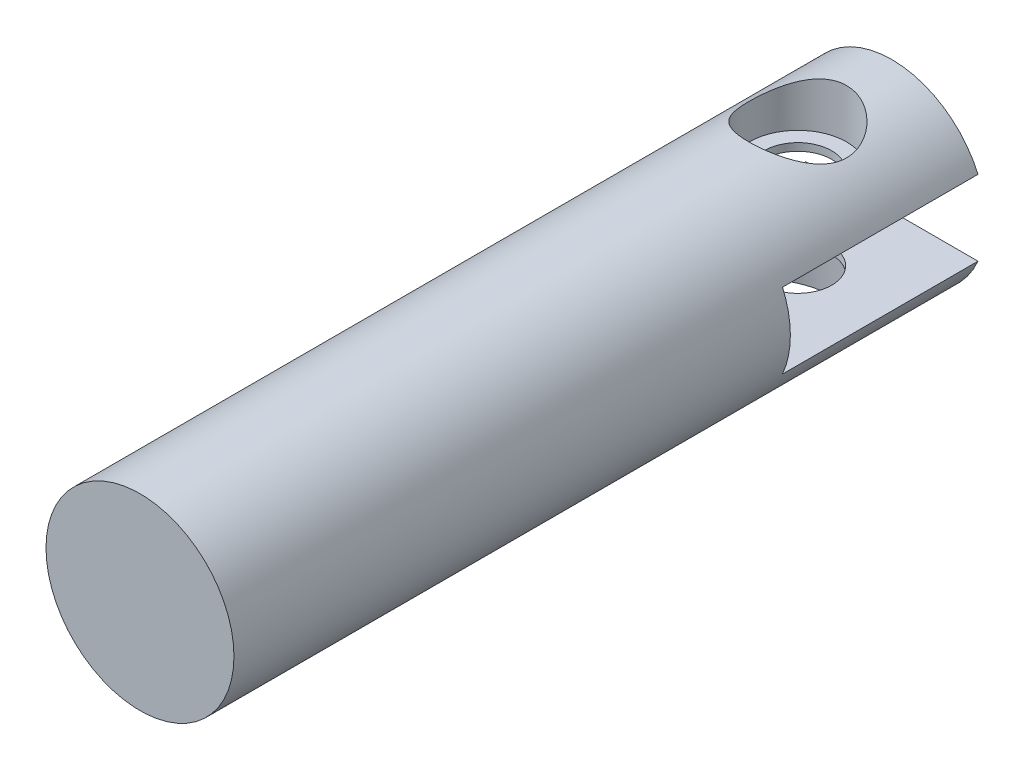
SolidWorks part; units mm, degrees
ref_plane "정면" through (0, 0, 0) normal (0, 0, 1) x (1, 0, 0)
ref_plane "윗면" through (0, 0, 0) normal (0, 1, 0) x (1, 0, 0)
ref_plane "우측면" through (0, 0, 0) normal (1, 0, 0) x (0, 0, -1)
sketch "스케치1" plane through (0, 0, 0) normal (0, 0, 1) x (1, 0, 0)
  circle A0 centre (0, 0) radius 12.5
  dimension "D1" = 25
extrude "보스-돌출1" add sketch "스케치1" against normal blind 100 contours A0
sketch "스케치2" plane through (0, 0, -100) normal (0, 0, -1) x (-1, 0, 0)
  line L0 (18.4039, 0) -> (-28.4221, 0) construction
  line L2 (11.4564, 5) -> (-11.4564, 5)
  line L4 (11.4564, -5) -> (-11.4564, -5)
  circle A1 centre (0, 0) radius 12.5 construction
  arc A5 (11.4564, -5) -> (11.4564, 5) centre (0, 0) ccw
  circle A6 centre (0, 0) radius 12.5
  arc A7 (-11.4564, 5) -> (-11.4564, -5) centre (0, 0) ccw
  dimension "D2" = 5
  dimension "D1" = 0
extrude "컷-돌출1" cut sketch "스케치2" against normal blind 26
ref_plane "평면2" through (12.5, 0, 0) normal (1, 0, 0) x (0, 0, -1)
sketch "스케치3" plane through (0, 0, 0) normal (0, 1, 0) x (1, 0, 0)
  line L0 (25.0967, 87.5) -> (-34.827, 87.5) construction
  line L2 (12.5, 0) -> (12.5, 74) construction
  line L3 (12.5, -11.7673) -> (12.5, 74) construction
  line L6 (12.5, 74) -> (11.4564, 74) construction
  circle A0 centre (0, 87.5) radius 4.5
  dimension "D1" = 9
  dimension "D2" = 13.5
extrude "컷-돌출2" cut sketch "스케치3" against normal blind 36.5348 and the other way blind 34
ref_plane "평면3" through (0, 6, 0) normal (0, -1, 0) x (-1, 0, 0)
sketch "스케치6" plane through (0, 6, 0) normal (0, 1, 0) x (1, 0, 0)
  circle A0 centre (0, 87.5) radius 6.5
  dimension "D1" = 13
extrude "컷-돌출5" cut sketch "스케치6" along normal blind 16
mirror "대칭 복사1" about plane through (0, 0, 0) normal (0, 1, 0) of "컷-돌출5"
